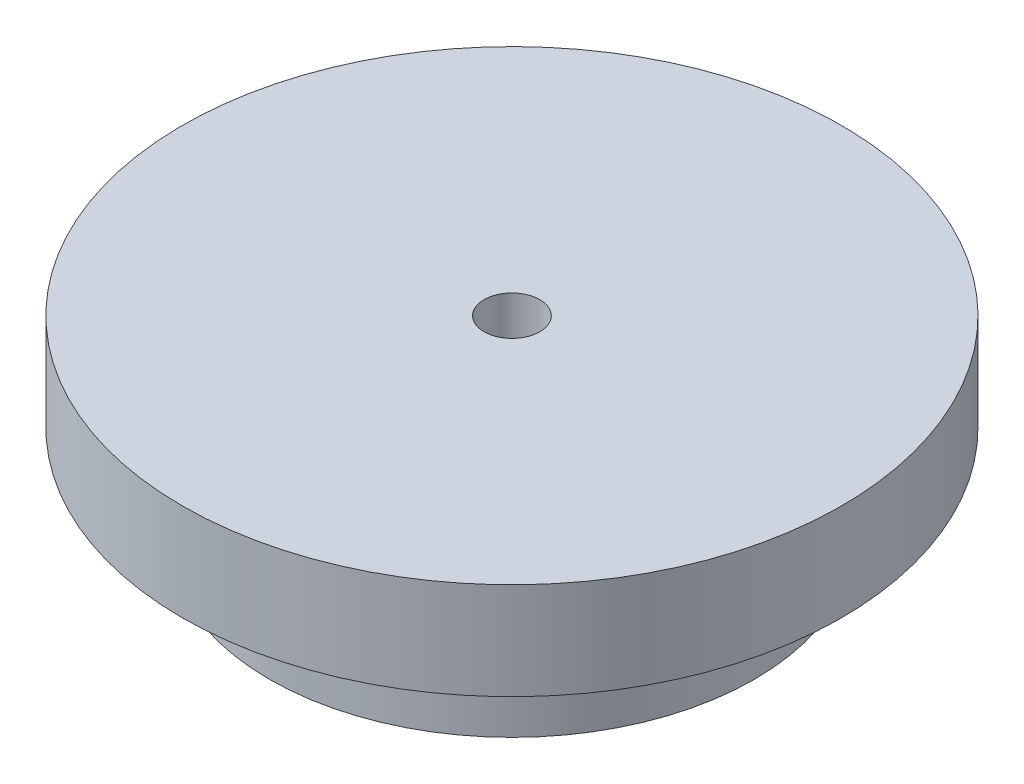
SolidWorks part; units mm, degrees
ref_plane "Front Plane" through (0, 0, 0) normal (0, 0, 1) x (1, 0, 0)
ref_plane "Top Plane" through (0, 0, 0) normal (0, 1, 0) x (1, 0, 0)
ref_plane "Right Plane" through (0, 0, 0) normal (1, 0, 0) x (0, 0, -1)
sketch "Sketch1" plane through (0, 0, 0) normal (0, 1, 0) x (1, 0, 0)
  line L0 (0, 5.5) -> (0, 4.5) construction
  line L1 (2.75, 4.7631) -> (2.25, 3.8971) construction
  line L2 (4.7631, 2.75) -> (3.8971, 2.25) construction
  line L3 (5.5, 0) -> (4.5, 0) construction
  line L4 (4.7631, -2.75) -> (3.8971, -2.25) construction
  line L5 (2.75, -4.7631) -> (2.25, -3.8971) construction
  line L6 (0, -5.5) -> (0, -4.5) construction
  line L7 (-2.75, -4.7631) -> (-2.25, -3.8971) construction
  line L8 (-4.7631, -2.75) -> (-3.8971, -2.25) construction
  line L9 (-5.5, 0) -> (-4.5, 0) construction
  line L10 (-4.7631, 2.75) -> (-3.8971, 2.25) construction
  line L11 (-2.75, 4.7631) -> (-2.25, 3.8971) construction
  line L12 (0, 4.5) -> (1, 5.5) construction
  line L13 (1, 5.5) -> (-1, 5.5) construction
  line L14 (-1, 5.5) -> (0, 4.5) construction
  line L15 (0, 4.5) -> (-0.9221, 5.4221)
  line L16 (0, 4.5) -> (0.9221, 5.4221)
  line L17 (2.25, 3.8971) -> (3.5097, 4.2346)
  line L18 (2.25, 3.8971) -> (1.9125, 5.1568)
  line L19 (3.8971, 2.25) -> (5.1568, 1.9125)
  line L20 (3.8971, 2.25) -> (4.2346, 3.5097)
  line L21 (4.5, 0) -> (5.4221, -0.9221)
  line L22 (4.5, 0) -> (5.4221, 0.9221)
  line L23 (3.8971, -2.25) -> (4.2346, -3.5097)
  line L24 (3.8971, -2.25) -> (5.1568, -1.9125)
  line L25 (2.25, -3.8971) -> (1.9125, -5.1568)
  line L26 (2.25, -3.8971) -> (3.5097, -4.2346)
  line L27 (0, -4.5) -> (-0.9221, -5.4221)
  line L28 (0, -4.5) -> (0.9221, -5.4221)
  line L29 (-2.25, -3.8971) -> (-3.5097, -4.2346)
  line L30 (-2.25, -3.8971) -> (-1.9125, -5.1568)
  line L31 (-3.8971, -2.25) -> (-5.1568, -1.9125)
  line L32 (-3.8971, -2.25) -> (-4.2346, -3.5097)
  line L33 (-4.5, 0) -> (-5.4221, 0.9221)
  line L34 (-4.5, 0) -> (-5.4221, -0.9221)
  line L35 (-3.8971, 2.25) -> (-4.2346, 3.5097)
  line L36 (-3.8971, 2.25) -> (-5.1568, 1.9125)
  line L37 (-2.25, 3.8971) -> (-1.9125, 5.1568)
  line L38 (-2.25, 3.8971) -> (-3.5097, 4.2346)
  circle A0 centre (0, 0) radius 2.75 construction
  circle A1 centre (0, 0) radius 5.5 construction
  arc A2 (0.9221, 5.4221) -> (1.9125, 5.1568) centre (0, 0) cw
  arc A3 (3.5097, 4.2346) -> (4.2346, 3.5097) centre (0, 0) cw
  arc A4 (5.4221, 0.9221) -> (5.1568, 1.9125) centre (0, 0) ccw
  arc A5 (5.1568, -1.9125) -> (5.4221, -0.9221) centre (0, 0) ccw
  arc A6 (3.5097, -4.2346) -> (4.2346, -3.5097) centre (0, 0) ccw
  arc A7 (0.9221, -5.4221) -> (1.9125, -5.1568) centre (0, 0) ccw
  arc A8 (-1.9125, -5.1568) -> (-0.9221, -5.4221) centre (0, 0) ccw
  arc A9 (-3.5097, -4.2346) -> (-4.2346, -3.5097) centre (0, 0) cw
  arc A10 (-5.1568, -1.9125) -> (-5.4221, -0.9221) centre (0, 0) cw
  arc A11 (-5.4221, 0.9221) -> (-5.1568, 1.9125) centre (0, 0) cw
  arc A12 (-4.2346, 3.5097) -> (-3.5097, 4.2346) centre (0, 0) cw
  arc A13 (-0.9221, 5.4221) -> (-1.9125, 5.1568) centre (0, 0) ccw
  circle A14 centre (0, 0) radius 25
  point P31 (0, 0)
  dimension "D1" = 5.5
  dimension "D2" = 11
  dimension "D5" = 50
  dimension "D4" = 1
  dimension "D3" = 12
extrude "Boss-Extrude1" add sketch "Sketch1" along normal blind 10
sketch "Sketch2" plane through (0, 10, 0) normal (0, 1, 0) x (1, 0, 0)
  circle A0 centre (0, 0) radius 2.875
  circle A1 centre (0, 0) radius 34
  dimension "D1" = 68
  dimension "D2" = 5.75
extrude "Boss-Extrude2" add sketch "Sketch2" along normal blind 10
